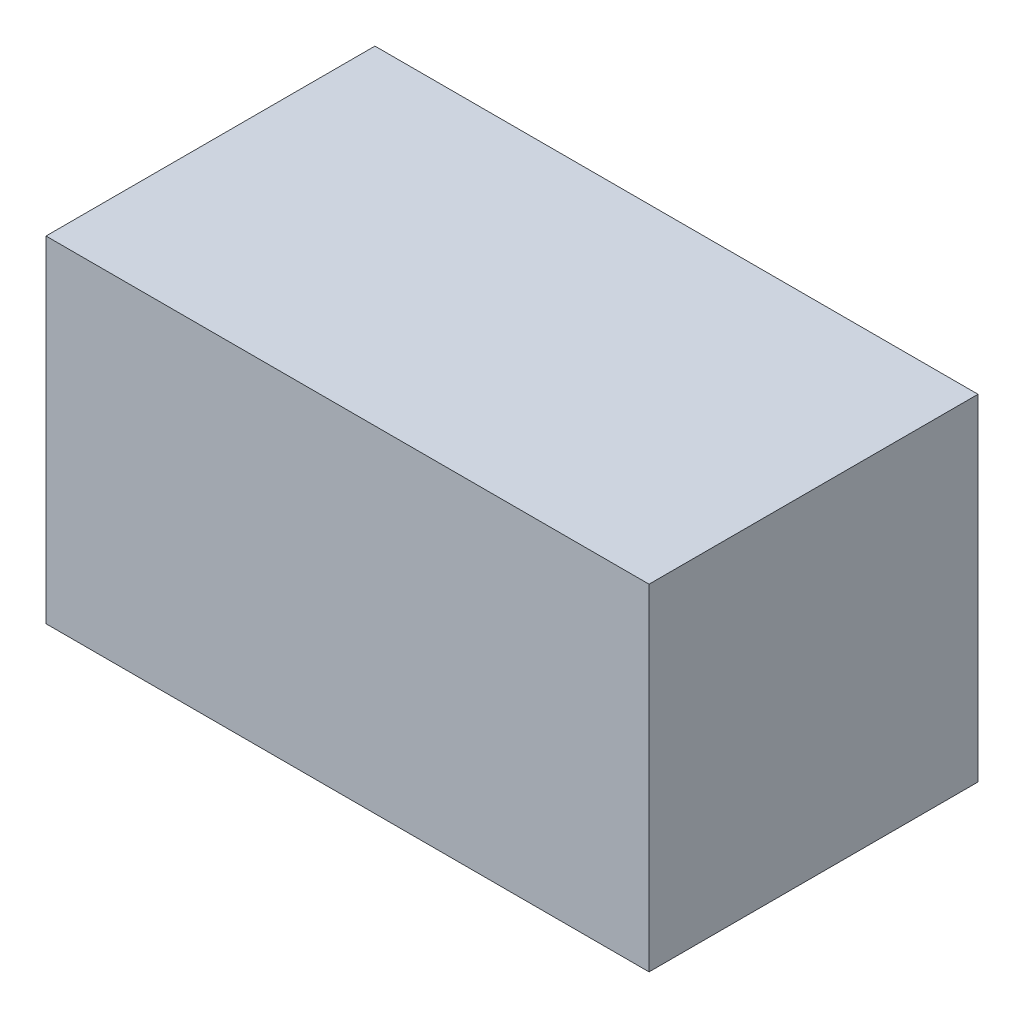
SolidWorks part; units mm, degrees
ref_plane "Front Plane" through (0, 0, 0) normal (0, 0, 1) x (1, 0, 0)
ref_plane "Top Plane" through (0, 0, 0) normal (0, 1, 0) x (1, 0, 0)
ref_plane "Right Plane" through (0, 0, 0) normal (1, 0, 0) x (0, 0, -1)
sketch "Sketch1" plane through (0, 0, 0) normal (0, 1, 0) x (1, 0, 0)
  line L1 (-88, -48) -> (88, -48)
  line L2 (-88, -48) -> (-88, 48)
  line L3 (-88, 48) -> (88, 48)
  line L4 (88, -48) -> (88, 48)
  line L5 (-88, -48) -> (88, 48) construction
  line L6 (-88, 48) -> (88, -48) construction
  point P0 (0, 0)
extrude "Boss-Extrude1" add sketch "Sketch1" along normal blind 98
